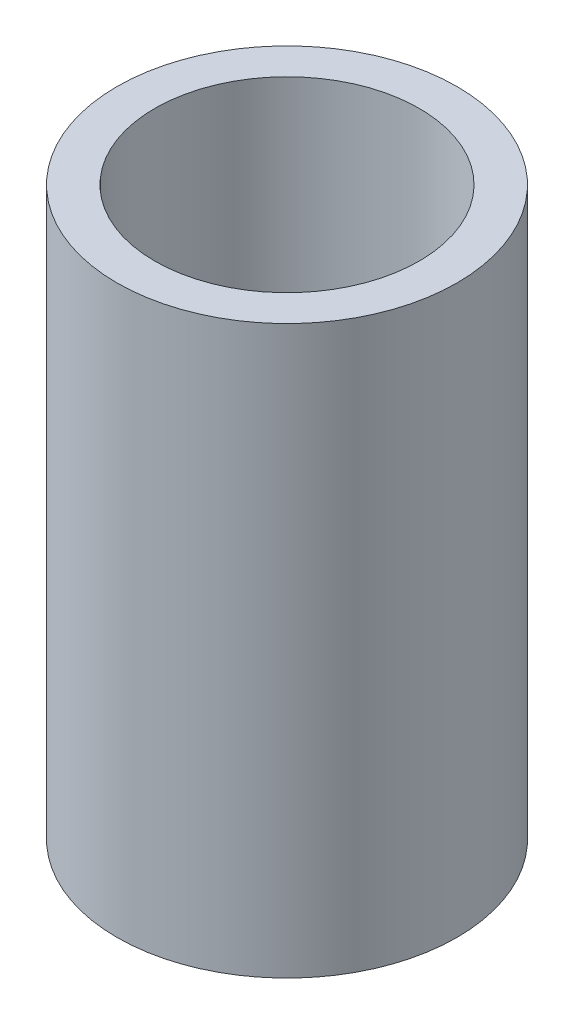
SolidWorks part; units mm, degrees
ref_plane "Front Plane" through (0, 0, 0) normal (0, 0, 1) x (1, 0, 0)
ref_plane "Top Plane" through (0, 0, 0) normal (0, 1, 0) x (1, 0, 0)
ref_plane "Right Plane" through (0, 0, 0) normal (1, 0, 0) x (0, 0, -1)
sketch "Sketch1" plane through (0, 0, 0) normal (0, 1, 0) x (1, 0, 0)
  circle A0 centre (0, 0) radius 28.575
  circle A1 centre (0, 0) radius 22.225
  dimension "D1" = 57.15
  dimension "D2" = 44.45
extrude "Boss-Extrude1" add sketch "Sketch1" along normal blind 95.25
